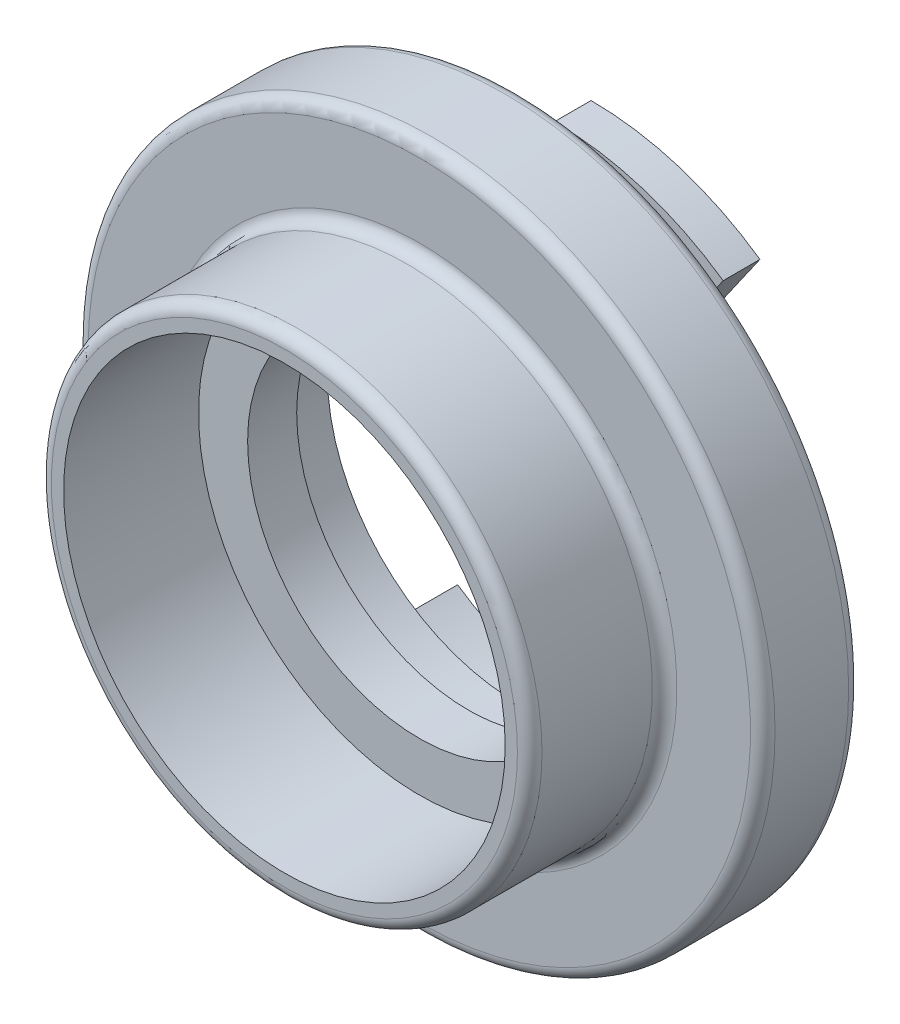
SolidWorks part; units mm, degrees
ref_plane "Front Plane" through (0, 0, 0) normal (0, 0, 1) x (1, 0, 0)
ref_plane "Top Plane" through (0, 0, 0) normal (0, 1, 0) x (1, 0, 0)
ref_plane "Right Plane" through (0, 0, 0) normal (1, 0, 0) x (0, 0, -1)
sketch "Sketch1" plane through (0, 0, 0) normal (0, 0, 1) x (1, 0, 0)
  circle A0 centre (0, 0) radius 25.4
  dimension "D1" = 50.8
extrude "Boss-Extrude1" add sketch "Sketch1" along normal blind 13.97
sketch "Sketch2" plane through (0, 0, 13.97) normal (0, 0, 1) x (1, 0, 0)
  circle A0 centre (0, 0) radius 22.86
  dimension "D1" = 45.72
extrude "Cut-Extrude1" cut sketch "Sketch2" against normal blind 25.4
sketch "Sketch3" plane through (0, 0, 0) normal (0, 0, -1) x (-1, 0, 0)
  circle A0 centre (0, 0) radius 35.56
  dimension "D1" = 71.12
extrude "Boss-Extrude2" add sketch "Sketch3" along normal blind 10.16
sketch "Sketch4" plane through (0, 0, -10.16) normal (0, 0, -1) x (-1, 0, 0)
  circle A0 centre (0, 0) radius 17.78
  dimension "D1" = 35.56
extrude "Cut-Extrude2" cut sketch "Sketch4" against normal blind 10.16
sketch "Sketch5" plane through (0, 0, -10.16) normal (0, 0, -1) x (-1, 0, 0)
  line L0 (0, 36.6763) -> (0, -38.6732) construction
  line L1 (0, 0) -> (15.9918, -22.9108) construction
  line L2 (0, 24.13) -> (0, 30.48)
  line L3 (13.8111, -19.7866) -> (15.9918, -22.9108)
  arc A0 (0, 30.48) -> (19.5746, 23.3638) centre (0, 0) cw
  circle A1 centre (0, 0) radius 35.56 construction
  arc A2 (19.5746, 23.3638) -> (21.5114, 19.6967) centre (16.0504, 19.1574) cw
  arc A3 (21.5114, 19.6967) -> (22.86, 16.0644) centre (29.0945, 20.4456) ccw
  arc A4 (22.86, 16.0644) -> (15.9918, -22.9108) centre (0, 0) cw
  arc A5 (0, -27.94) -> (15.9918, -22.9108) centre (0, 0) ccw construction
  arc A6 (13.8111, -19.7866) -> (0, 24.13) centre (0, 0) ccw
  circle A7 centre (0, 0) radius 35.56 construction
  dimension "D1" = 20.828
  dimension "D2" = 30.48
  dimension "D3" = 22.86
  dimension "D4" = 3.81
  dimension "D5" = 16.764
  dimension "D6" = 24.13
extrude "Cut-Extrude3" cut sketch "Sketch5" against normal blind 7.62
ref_plane "Plane1" through (0, 0, -7.62) normal (0, 0, -1) x (-1, 0, 0)
sketch "Sketch7" plane through (0, 0, -7.62) normal (0, 0, -1) x (-1, 0, 0)
  line L0 (0, 0) -> (15.9918, -22.9108) construction
  line L1 (17.4456, -24.9936) -> (15.9918, -22.9108)
  arc A0 (19.5746, 23.3638) -> (17.4456, -24.9936) centre (0, 0) cw
  circle A1 centre (0, 0) radius 35.56 construction
  arc A2 (15.9918, -22.9108) -> (22.86, 16.0644) centre (0, 0) ccw
  arc A3 (15.9918, -22.9108) -> (22.86, 16.0644) centre (0, 0) ccw construction
  arc A4 (22.86, 16.0644) -> (21.5114, 19.6967) centre (29.0945, 20.4456) cw
  arc A5 (21.5114, 19.6967) -> (19.5746, 23.3638) centre (16.0504, 19.1574) ccw
extrude "Cut-Extrude4" cut sketch "Sketch7" against normal blind 5.08
sketch "Sketch8" plane through (0, 0, -10.16) normal (0, 0, -1) x (-1, 0, 0)
  line L0 (0, 0) -> (0, -41.8815) construction
  line L1 (0, -27.94) -> (0, -24.13)
  line L2 (13.8111, -19.7866) -> (15.9918, -22.9108) construction
  line L3 (13.8111, -19.7866) -> (15.9918, -22.9108)
  arc A0 (0, -27.94) -> (15.9918, -22.9108) centre (0, 0) ccw
  circle A2 centre (0, 0) radius 35.56 construction
  arc A3 (0, -24.13) -> (13.8111, -19.7866) centre (0, 0) ccw
  dimension "D1" = 24.13
  dimension "D2" = 3.81
extrude "Boss-Extrude3" add sketch "Sketch8" along normal blind 3.81
sketch "Sketch9" plane through (0, 0, -13.97) normal (0, 0, -1) x (-1, 0, 0)
  line L0 (0, -24.13) -> (0, -30.48)
  line L1 (0, 0) -> (15.9918, -22.9108) construction
  line L2 (13.8111, -19.7866) -> (17.4456, -24.9936)
  arc A0 (0, -24.13) -> (13.8111, -19.7866) centre (0, 0) ccw
  arc A1 (0, -24.13) -> (13.8111, -19.7866) centre (0, 0) ccw construction
  arc A2 (0, -30.48) -> (17.4456, -24.9936) centre (0, 0) ccw
  dimension "D1" = 6.35
extrude "Boss-Extrude4" add sketch "Sketch9" along normal blind 3.81
fillet "Fillet1" radius 1.27 1 edges at (-35.56, 0, -10.16)
fillet "Fillet2" radius 1.27 3 edges at (25.4, 0, 13.97) (25.4, 0, 0) (-35.56, 0, 0)
sketch "Sketch10" plane through (0, 0, -10.16) normal (0, 0, -1) x (-1, 0, 0)
  line L0 (0, 30.48) -> (0, 24.13) construction
  line L3 (0, 0) -> (-16.002, 22.9037) construction
  line L4 (-13.8199, 19.7805) -> (-16.002, 22.9037)
  line L5 (0, 27.94) -> (0, 24.13)
  arc A0 (0, 24.13) -> (-13.8199, 19.7805) centre (0, 0) ccw
  arc A1 (0, 27.94) -> (-16.002, 22.9037) centre (0, 0) ccw
  circle A2 centre (0, 0) radius 35.56 construction
  dimension "D2" = 16.002
  dimension "D1" = 3.81
extrude "Boss-Extrude5" add sketch "Sketch10" along normal blind 3.81
sketch "Sketch11" plane through (0, 0, -13.97) normal (0, 0, -1) x (-1, 0, 0)
  line L1 (-13.8199, 19.7805) -> (-17.4865, 25.0285)
  line L2 (0, 24.13) -> (0, 30.5321)
  line L3 (-16.002, 22.9037) -> (-13.8199, 19.7805) construction
  arc A0 (-13.8199, 19.7805) -> (0, 24.13) centre (0, 0) cw
  arc A1 (0, 24.13) -> (-13.8199, 19.7805) centre (0, 0) ccw construction
  arc A2 (-17.4865, 25.0285) -> (0, 30.5321) centre (0, 0) cw
  circle A3 centre (0, 0) radius 34.29 construction
  dimension "D2" = 6.4021
extrude "Boss-Extrude6" add sketch "Sketch11" along normal blind 3.81
sketch "Sketch12" plane through (0, 0, -10.16) normal (0, 0, -1) x (-1, 0, 0)
  circle A0 centre (0, 0) radius 15.494
  circle A1 centre (0, 0) radius 19.685
  dimension "D1" = 30.988
  dimension "D2" = 39.37
extrude "Cut-Extrude5" cut sketch "Sketch12" against normal blind 5.08
sketch "Sketch13" plane through (0, 0, -10.16) normal (0, 0, -1) x (-1, 0, 0)
  line L0 (-16.002, 22.9037) -> (-13.8199, 19.7805)
  line L1 (0, -30.48) -> (0, -24.13)
  arc A0 (0, -30.48) -> (-19.5746, -23.3638) centre (0, 0) cw
  circle A1 centre (0, 0) radius 34.29 construction
  arc A2 (-19.5746, -23.3638) -> (-21.5114, -19.6967) centre (-16.0504, -19.1574) cw
  arc A3 (-21.5114, -19.6967) -> (-22.86, -16.0644) centre (-29.0945, -20.4456) ccw
  arc A4 (-22.86, -16.0644) -> (-16.002, 22.9037) centre (0, 0) cw
  circle A5 centre (0, 0) radius 35.56 construction
  arc A6 (0, -24.13) -> (-13.8199, 19.7805) centre (0, 0) cw
  dimension "D1" = 20.828
  dimension "D2" = 22.86
extrude "Cut-Extrude6" cut sketch "Sketch13" against normal blind 7.62
sketch "Sketch15" plane through (0, 0, -7.62) normal (0, 0, -1) x (-1, 0, 0)
  line L0 (-17.4865, 25.0285) -> (-13.8199, 19.7805) construction
  line L1 (-17.4567, 24.9859) -> (-16.002, 22.9037)
  arc A0 (-19.5746, -23.3638) -> (-17.4567, 24.9859) centre (0, 0) cw
  arc A1 (-19.5746, -23.3638) -> (-21.5114, -19.6967) centre (-16.0504, -19.1574) cw
  arc A2 (-21.5114, -19.6967) -> (-22.86, -16.0644) centre (-29.0945, -20.4456) ccw
  arc A3 (-22.86, -16.0644) -> (-16.002, 22.9037) centre (0, 0) cw
extrude "Cut-Extrude7" cut sketch "Sketch15" against normal blind 5.08 contours A3 L1 A0 A1 A2
